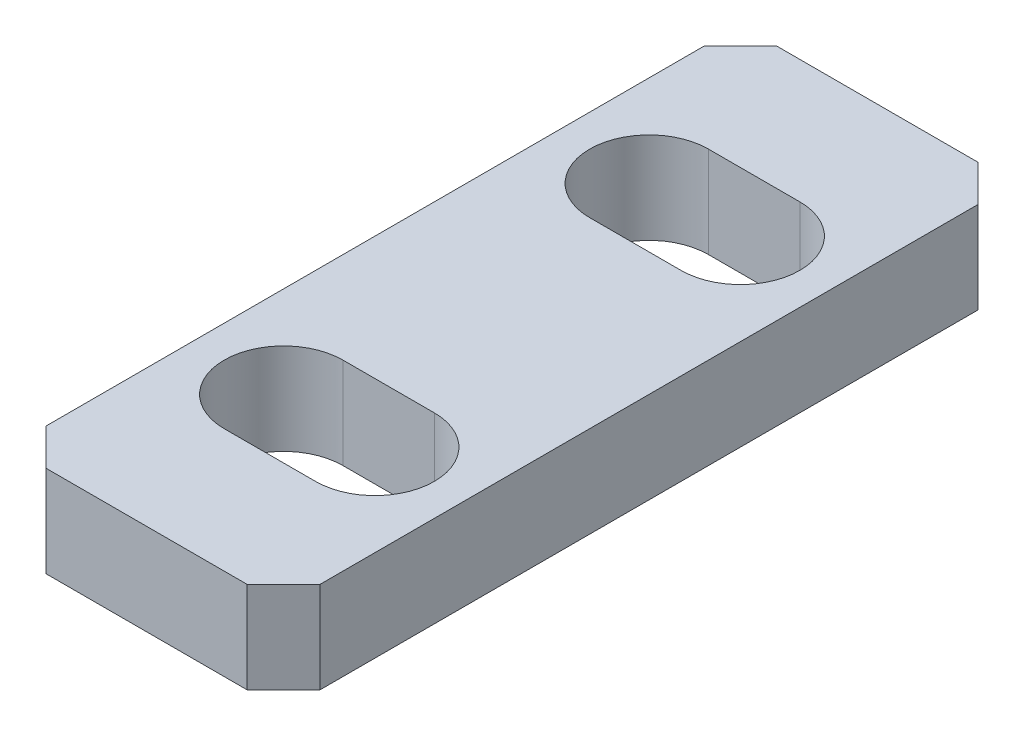
SolidWorks part; units mm, degrees
ref_plane "Front Plane" through (0, 0, 0) normal (0, 0, 1) x (1, 0, 0)
ref_plane "Top Plane" through (0, 0, 0) normal (0, 1, 0) x (1, 0, 0)
ref_plane "Right Plane" through (0, 0, 0) normal (1, 0, 0) x (0, 0, -1)
sketch "Sketch1" plane through (0, 0, 0) normal (0, 1, 0) x (1, 0, 0)
  line L0 (0, 38) -> (2, 40)
  line L1 (2, 0) -> (13, 0)
  line L2 (0, 2) -> (0, 38)
  line L3 (2, 40) -> (13, 40)
  line L4 (15, 2) -> (15, 38)
  line L5 (13, 40) -> (15, 38)
  line L6 (13, 0) -> (15, 2)
  line L7 (0, 2) -> (2, 0)
  line L8 (5, 30) -> (10, 30) construction
  line L9 (5, 33.25) -> (10, 33.25)
  line L10 (5, 26.75) -> (10, 26.75)
  line L11 (5, 10) -> (10, 10) construction
  line L12 (5, 13.25) -> (10, 13.25)
  line L13 (5, 6.75) -> (10, 6.75)
  arc A0 (5, 33.25) -> (5, 26.75) centre (5, 30) ccw
  arc A1 (10, 26.75) -> (10, 33.25) centre (10, 30) ccw
  arc A2 (5, 13.25) -> (5, 6.75) centre (5, 10) ccw
  arc A3 (10, 6.75) -> (10, 13.25) centre (10, 10) ccw
  point P0 (0, 0)
  point P1 (15, 40)
  point P2 (0, 40)
  point P3 (15, 0)
  point P4 (7.5, 30)
  point P20 (0, 0)
  point P21 (0, 0)
  point P22 (8.9773, 34.6495)
  point P23 (7.5, 40)
  point P24 (0, 0)
  point P25 (0, 0)
  point P26 (7.5, 10)
  point P33 (6.1325, 23.3964)
  point P34 (7.2226, 17.0297)
  point P35 (0, 0)
  point P36 (0, 0)
  dimension "D1" = 40
  dimension "D2" = 15
  dimension "D3" = 2
  dimension "D4" = 45
  dimension "D5" = 2
  dimension "D6" = 45
  dimension "D7" = 2
  dimension "D8" = 45
  dimension "D9" = 2
  dimension "D10" = 45
  dimension "D11" = 5
  dimension "D12" = 10
  dimension "D13" = 6.5
  dimension "D14" = 20
  dimension "D15" = 6.5
extrude "Boss-Extrude1" add sketch "Sketch1" along normal blind 5
